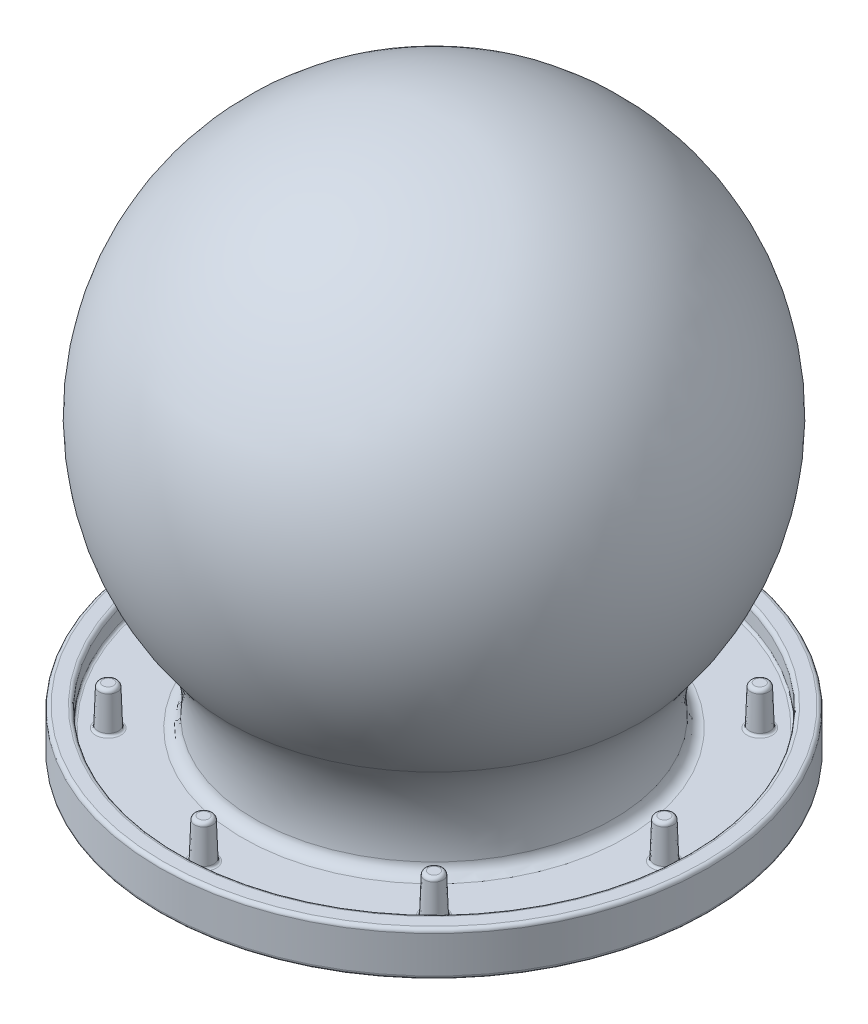
SolidWorks part; units mm, degrees
ref_plane "Front Plane" through (0, 0, 0) normal (0, 0, 1) x (1, 0, 0)
ref_plane "Top Plane" through (0, 0, 0) normal (0, 1, 0) x (1, 0, 0)
ref_plane "Right Plane" through (0, 0, 0) normal (1, 0, 0) x (0, 0, -1)
sketch "Sketch1" plane through (0, 0, 0) normal (0, 0, 1) x (1, 0, 0)
  line L0 (-39, 0) -> (0, 0) construction
  line L1 (0, 0) -> (0, 110) construction
  line L2 (-39, 0) -> (-52, 0)
  line L3 (-52, 0) -> (-52, 4)
  line L4 (-52, 4) -> (-42, 4) construction
  line L5 (0, 110) -> (0, 108.5) construction
  line L6 (0, 110) -> (40.3173, 110) construction
  line L7 (-52, 4) -> (-56, 4)
  line L8 (-56, 4) -> (-56, -5)
  line L9 (-56, -5) -> (-30.5655, -5)
  line L10 (-30.5655, -5) -> (-30.5655, 40)
  line L11 (0, 102.5) -> (0, 108.5)
  line L12 (0, 102.5) -> (-26.7419, 102.5) construction
  arc A0 (-38.0283, 8.4752) -> (-42, 4) centre (-42, 8) cw construction
  arc A1 (-38.0283, 8.4752) -> (-43.2103, 20.9725) centre (-62.8513, 5.5054) ccw construction
  arc A2 (-43.2103, 20.9725) -> (0, 110) centre (0, 55) cw construction
  arc A3 (0, 108.5) -> (-42.0318, 21.9005) centre (0, 55) ccw
  arc A4 (-42.0318, 21.9005) -> (-36.5655, 2.1429) centre (-62.8513, 5.5054) cw
  arc A5 (-36.5655, 2.1429) -> (-39, 0) centre (-39, 2.4543) cw
  arc A6 (-30.5655, 40) -> (-13.9776, 95) centre (68.9094, 40) cw
  arc A7 (-13.9776, 95) -> (0, 102.5) centre (0, 85.7251) cw
  dimension "D6" = 55
  dimension "D7" = 4
  dimension "D8" = 25
  dimension "D1" = 52
  dimension "D2" = 13
  dimension "D3" = 10
  dimension "D4" = 4
  dimension "D5" = 110
  dimension "D9" = 1.5
  dimension "D10" = 6
  dimension "D11" = 6
  dimension "D12" = 5
  dimension "D13" = 4
  dimension "D14" = 45
  dimension "D15" = 55
revolve "Revolve1" add sketch "Sketch1" angle 360 about L5
sketch "Sketch2" plane through (0, 0, 0) normal (0, 1, 0) x (-1, 0, 0)
  line L0 (0, 0) -> (0, 47) construction
  line L1 (0, 47) -> (0, 52) construction
  circle A0 centre (0, 47) radius 2.1
  circle A1 centre (0, 0) radius 52 construction
  dimension "D2" = 4.2
  dimension "D1" = 5
extrude "Boss-Extrude1" add sketch "Sketch2" along normal blind 8 draft 2
fillet "Fillet1" radius 0.75 1 edges at (-1.8206, 8, 47)
pattern_circular "CirPattern1" count 8 over 360 about axis through (0, 0, 0) along (0, 1, 0) of "Fillet1", "Boss-Extrude1"
fillet "Fillet2" radius 0.75 4 edges at (-56, -5, 0) (-30.5655, -5, 0) (-52, 4, 0) (-56, 4, 0)
fillet "Fillet3" radius 0.5 9 edges at (-34.7189, 0, 31.7491) (-31.7491, 0, -34.7189) (34.7189, 0, -31.7491) (31.7491, 0, 34.7189) (-52, 0, 0) (-2.1, 0, 47) (47, 0, 2.1) (2.1, 0, -47) (-47, 0, -2.1)
